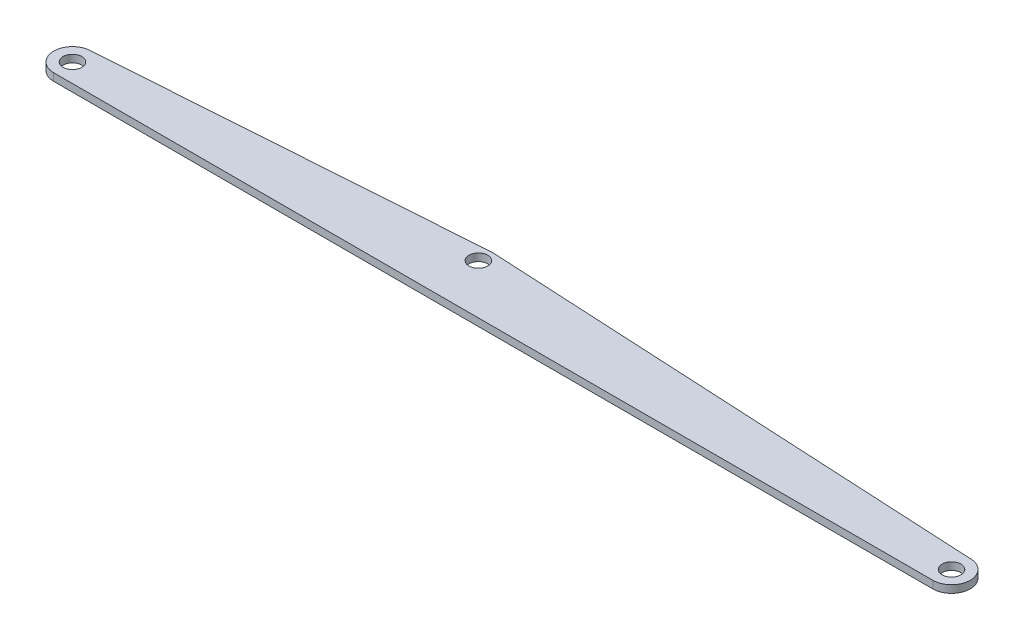
SolidWorks part; units mm, degrees
ref_plane "Front Plane" through (0, 0, 0) normal (0, 0, 1) x (1, 0, 0)
ref_plane "Top Plane" through (0, 0, 0) normal (0, 1, 0) x (1, 0, 0)
ref_plane "Right Plane" through (0, 0, 0) normal (1, 0, 0) x (0, 0, -1)
sketch "Sketch2" plane through (0, 0, 0) normal (0, 1, 0) x (1, 0, 0)
  line L0 (0, 0) -> (0, 12.7) construction
  line L1 (0, 0) -> (0, -12.7) construction
  line L2 (0, 0) -> (12.7, 0) construction
  line L3 (0, 0) -> (-595.5, 0) construction
  line L4 (-595.5, 0) -> (-608.2, 0) construction
  line L5 (-595.5, 0) -> (-341.4598, 20.9188) construction
  line L6 (-595.5, 0) -> (-595.5, -12.7) construction
  line L7 (-595.5, 0) -> (-595.5, 12.7) construction
  line L8 (-595.5, -12.7) -> (0, -12.7)
  line L9 (-595.5, 12.7) -> (-342.1244, 30.4206)
  line L11 (0, 12.7) -> (-340.9652, 30.431)
  circle A0 centre (0, 0) radius 6.35
  arc A1 (0, 12.7) -> (0, -12.7) centre (0, 0) cw
  circle A2 centre (-595.5, 0) radius 6.35
  circle A3 centre (-341.4598, 20.9188) radius 6.35
  arc A4 (-595.5, 12.7) -> (-595.5, -12.7) centre (-595.5, 0) ccw
  arc A5 (-340.9652, 30.431) -> (-342.1244, 30.4206) centre (-341.4598, 20.9188) ccw
  point P15 (0, 0)
  point P16 (0, 0)
  dimension "D1" = 12.7
  dimension "D6" = 12.7
  dimension "D8" = 12.7
  dimension "D11" = 19.05
  dimension "D2" = 12.7
  dimension "D3" = 12.7
  dimension "D4" = 12.7
  dimension "D5" = 595.5
  dimension "D7" = 12.7
  dimension "D9" = 254.9
  dimension "D10" = 4.707
extrude "Boss-Extrude1" add sketch "Sketch2" against normal blind 5.08
